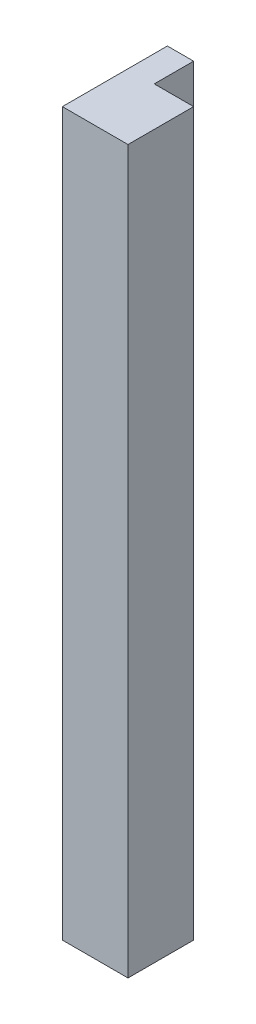
SolidWorks part; units mm, degrees
ref_plane "Front Plane" through (0, 0, 0) normal (0, 0, 1) x (1, 0, 0)
ref_plane "Top Plane" through (0, 0, 0) normal (0, 1, 0) x (1, 0, 0)
ref_plane "Right Plane" through (0, 0, 0) normal (1, 0, 0) x (0, 0, -1)
sketch "Sketch1" plane through (0, 0, 0) normal (0, 1, 0) x (1, 0, 0)
  line L1 (2.5, -4) -> (-2.5, -4)
  line L2 (2.5, -4) -> (2.5, 4)
  line L3 (2.5, 4) -> (-2.5, 4)
  line L4 (-2.5, -4) -> (-2.5, 4)
  line L5 (2.5, -4) -> (-2.5, 4) construction
  line L6 (2.5, 4) -> (-2.5, -4) construction
  point P0 (0, 0)
  dimension "D1" = 5
  dimension "D2" = 8
extrude "Boss-Extrude1" add sketch "Sketch1" along normal blind 55
ref_plane "Plane1" through (0, 0, 0) normal (0, -1, 0) x (-1, 0, 0)
sketch "Sketch2" plane through (0, 0, 0) normal (0, -1, 0) x (-1, 0, 0)
  line L1 (-2.5, 4) -> (0.5, 4)
  line L2 (-2.5, 4) -> (-2.5, 1)
  line L3 (-2.5, 1) -> (0.5, 1)
  line L4 (0.5, 4) -> (0.5, 1)
  dimension "D1" = 3
  dimension "D2" = 3
extrude "Cut-Extrude1" cut sketch "Sketch2" against normal blind 55
